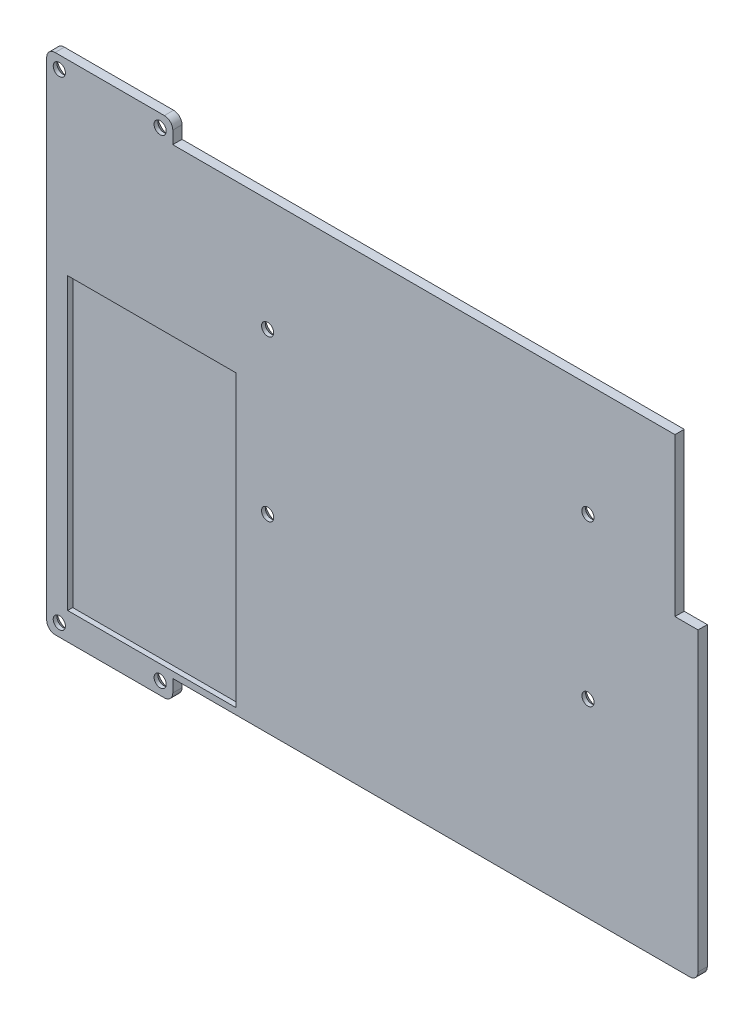
SolidWorks part; units mm, degrees
ref_plane "Front Plane" through (0, 0, 0) normal (0, 0, 1) x (1, 0, 0)
ref_plane "Top Plane" through (0, 0, 0) normal (0, 1, 0) x (1, 0, 0)
ref_plane "Right Plane" through (0, 0, 0) normal (1, 0, 0) x (0, 0, -1)
sketch "Sketch1" plane through (0, 0, 0) normal (0, 0, 1) x (1, 0, 0)
  line L1 (2, -60) -> (28, -60)
  line L2 (0, -58) -> (0, 58)
  line L3 (2, 60) -> (28, 60)
  line L4 (155, -53) -> (155, 17.5)
  line L9 (153, -55) -> (30, -55)
  line L12 (30, -55) -> (30, -58)
  line L13 (149.5, 55) -> (30, 55)
  line L16 (30, 55) -> (30, 58)
  line L18 (149.5, 55) -> (149.5, 17.5)
  line L19 (149.5, 17.5) -> (155, 17.5)
  arc A0 (2, -60) -> (0, -58) centre (2, -58) cw
  arc A3 (0, 58) -> (2, 60) centre (2, 58) cw
  arc A4 (153, -55) -> (155, -53) centre (153, -53) ccw
  arc A6 (28, 60) -> (30, 58) centre (28, 58) cw
  arc A7 (28, -60) -> (30, -58) centre (28, -58) ccw
  point P6 (0, -60)
  point P7 (155, -55)
  point P9 (155, -60)
  point P12 (0, 0)
  point P23 (30, 60)
  point P26 (30, -60)
  dimension "D3" = 2
  dimension "D8" = 2
  dimension "D12" = 70.5
  dimension "D1" = 155
  dimension "D2" = 116
  dimension "D4" = 125
  dimension "D5" = 5
  dimension "D6" = 5.5
  dimension "D7" = 5
  dimension "D9" = 37.5
  dimension "D10" = 3
  dimension "D11" = 26
extrude "Boss-Extrude1" add sketch "Sketch1" along normal blind 2.2
hole_wizard "CSK for M2.5 Countersunk Flat Head Screw1" positions "3DSketch1" profile "Sketch2" countersink size "M2.5" standard "ISO" end condition through all
sketch3d "3DSketch1"
  line L0 (149.5, 55, 0) -> (30, 55, 0) construction
  line L1 (155, -53, 0) -> (155, 17.5, 0) construction
  point P0 (52.575, 28.25, 0)
  point P2 (128.8, 28.25, 0)
  point P4 (128.8, -9.85, 0)
  point P6 (52.575, -9.85, 0)
  dimension "D1" = 26.75
  dimension "D2" = 102.425
  dimension "D3" = 76.225
  dimension "D4" = 38.1
sketch "Sketch2" plane through (52.575, 28.25, 0) normal (1, 0, 0) x (0, 1, 0)
  line L0 (0, 0) -> (0, 2.2)
  line L1 (0, 2.2) -> (1.45, 2.2)
  line L2 (1.45, 2.2) -> (1.45, 1.3)
  line L3 (1.45, 1.3) -> (2.75, 0)
  line L5 (2.75, 0) -> (0, 0)
  line L6 (-1.45, 1.3) -> (-2.75, 0) construction
  line L11 (0, -6.35) -> (0, 107.95) construction
  dimension "Thru Hole Dia." = 2.9
  dimension "Thru Hole Depth" = 2.2
  dimension "Near C'Sink Dia." = 5.5
  dimension "Near C'Sink Angle" = 90
hole_wizard "CSK for M2.5 Countersunk Flat Head Screw2" positions "3DSketch2" profile "Sketch3" countersink size "M2.5" standard "ISO" end condition through all
sketch3d "3DSketch2"
  line L0 (28, 60, 0) -> (2, 60, 0) construction
  line L1 (30, 55, 0) -> (30, 58, 0) construction
  line L2 (0, 58, 0) -> (0, -58, 0) construction
  line L4 (2, -60, 0) -> (28, -60, 0) construction
  point P0 (27, 57, 0)
  point P2 (3, 57, 0)
  point P4 (27, -57, 0)
  point P6 (3, -57, 0)
  dimension "D1" = 3
  dimension "D2" = 3
  dimension "D3" = 3
  dimension "D4" = 3
sketch "Sketch3" plane through (27, 57, 0) normal (1, 0, 0) x (0, 1, 0)
  line L0 (0, 0) -> (0, 2.2)
  line L1 (0, 2.2) -> (1.45, 2.2)
  line L2 (1.45, 2.2) -> (1.45, 1.3)
  line L3 (1.45, 1.3) -> (2.75, 0)
  line L5 (2.75, 0) -> (0, 0)
  line L6 (-1.45, 1.3) -> (-2.75, 0) construction
  line L11 (0, -6.35) -> (0, 107.95) construction
  dimension "Thru Hole Dia." = 2.9
  dimension "Thru Hole Depth" = 2.2
  dimension "Near C'Sink Dia." = 5.5
  dimension "Near C'Sink Angle" = 90
sketch "Sketch4" plane through (0, 0, 2.2) normal (0, 0, 1) x (1, 0, 0)
  line L0 (0, 58) -> (0, -58) construction
  line L1 (5, 15.5) -> (45, 15.5)
  line L2 (5, 15.5) -> (5, -53.5)
  line L3 (5, -53.5) -> (45, -53.5)
  line L4 (45, 15.5) -> (45, -53.5)
  line L5 (30, -55) -> (153, -55) construction
  dimension "D1" = 40
  dimension "D2" = 69
  dimension "D3" = 5
  dimension "D4" = 1.5
extrude "Cut-Extrude1" cut sketch "Sketch4" against normal blind 1.2 and the other way through all
